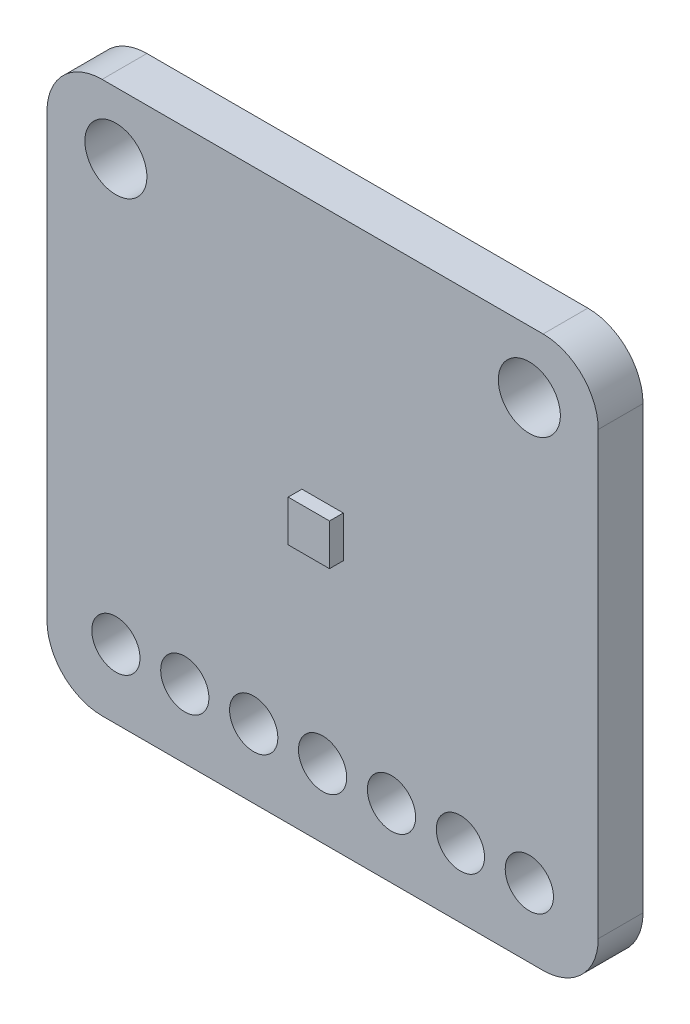
SolidWorks part; units mm, degrees
ref_plane "Front Plane" through (0, 0, 0) normal (0, 0, 1) x (1, 0, 0)
ref_plane "Top Plane" through (0, 0, 0) normal (0, 1, 0) x (1, 0, 0)
ref_plane "Right Plane" through (0, 0, 0) normal (1, 0, 0) x (0, 0, -1)
sketch "Sketch1" plane through (0, 0, 0) normal (0, 0, 1) x (1, 0, 0)
  line L1 (-8.0579, 8.6728) -> (8.1981, 8.6728)
  line L2 (-10.0899, 6.6408) -> (-10.0899, -9.6152)
  line L3 (-8.0579, -11.6472) -> (8.1981, -11.6472)
  line L4 (10.2301, 6.6408) -> (10.2301, -9.6152)
  arc A0 (8.1981, -11.6472) -> (10.2301, -9.6152) centre (8.1981, -9.6152) ccw
  arc A1 (-10.0899, -9.6152) -> (-8.0579, -11.6472) centre (-8.0579, -9.6152) ccw
  arc A2 (-8.0579, 8.6728) -> (-10.0899, 6.6408) centre (-8.0579, 6.6408) ccw
  arc A3 (8.1981, 8.6728) -> (10.2301, 6.6408) centre (8.1981, 6.6408) cw
  circle A4 centre (-7.5499, 6.3868) radius 1.143
  circle A5 centre (7.6901, 6.3868) radius 1.143
  circle A6 centre (0.0701, -9.1072) radius 0.889
  circle A7 centre (2.6101, -9.1072) radius 0.889
  circle A8 centre (5.1501, -9.1072) radius 0.889
  circle A9 centre (7.6901, -9.1072) radius 0.889
  circle A10 centre (-2.4699, -9.1072) radius 0.889
  circle A11 centre (-5.0099, -9.1072) radius 0.889
  circle A12 centre (-7.5499, -9.1072) radius 0.889
  point P6 (10.2301, -11.6472)
  point P11 (-10.0899, 8.6728)
  point P14 (10.2301, 8.6728)
  dimension "D3" = 2.032
  dimension "D4" = 2.54
  dimension "D5" = 2.54
  dimension "D6" = 2.286
  dimension "D7" = 2.54
  dimension "D1" = 20.32
  dimension "D2" = 20.32
  dimension "D8" = 2.286
  dimension "D9" = 4
  dimension "D10" = 4
extrude "Boss-Extrude1" add sketch "Sketch1" along normal blind 1.651
sketch "Sketch2" plane through (0, 0, 1.651) normal (0, 0, 1) x (1, 0, 0)
  line L0 (-10.0899, 6.6408) -> (-10.0899, -9.6152) construction
  line L1 (-0.6919, -0.7252) -> (0.8321, -0.7252)
  line L2 (-0.6919, -0.7252) -> (-0.6919, -2.2492)
  line L3 (-0.6919, -2.2492) -> (0.8321, -2.2492)
  line L4 (0.8321, -0.7252) -> (0.8321, -2.2492)
  line L5 (-8.0579, -11.6472) -> (8.1981, -11.6472) construction
  dimension "D1" = 1.524
  dimension "D2" = 1.524
  dimension "D3" = 9.398
  dimension "D4" = 9.398
extrude "Boss-Extrude2" add sketch "Sketch2" along normal blind 0.508
